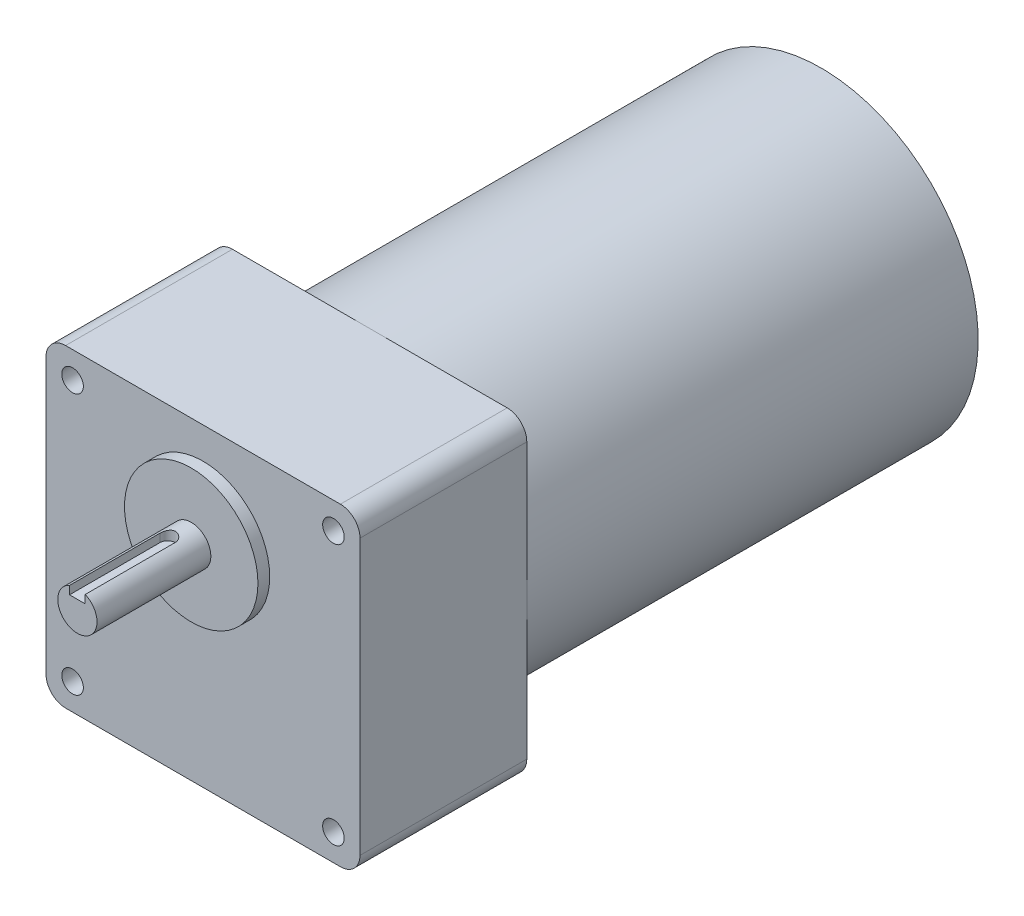
SolidWorks part; units mm, degrees
ref_plane "정면" through (0, 0, 0) normal (0, 0, 1) x (1, 0, 0)
ref_plane "윗면" through (0, 0, 0) normal (0, 1, 0) x (1, 0, 0)
ref_plane "우측면" through (0, 0, 0) normal (1, 0, 0) x (0, 0, -1)
sketch "스케치1" plane through (0, 0, 0) normal (0, 0, 1) x (1, 0, 0)
  line L1 (-40, 40) -> (40, 40)
  line L2 (-40, 40) -> (-40, -40)
  line L3 (-40, -40) -> (40, -40)
  line L4 (40, 40) -> (40, -40)
  point P0 (0, 0)
  dimension "D1" = 80
  dimension "D2" = 80
extrude "보스-돌출1" add sketch "스케치1" along normal blind 10
sketch "스케치2" plane through (0, 0, 10) normal (0, 0, 1) x (1, 0, 0)
  circle A0 centre (0, 15) radius 17
extrude "보스-돌출2" add sketch "스케치2" along normal blind 3
sketch "스케치3" plane through (0, 0, 13) normal (0, 0, 1) x (1, 0, 0)
  circle A0 centre (0, 15) radius 5
extrude "보스-돌출3" add sketch "스케치3" along normal blind 29
sketch "스케치4" plane through (0, 0, 42) normal (0, 0, 1) x (1, 0, 0)
  line L1 (0, 17.5) -> (-2, 17.5)
  line L2 (0, 17.5) -> (2, 17.5)
  line L3 (-2, 17.5) -> (-2, 20.9127)
  line L4 (-2, 20.9127) -> (2, 20.9127)
  line L5 (2, 20.9127) -> (2, 17.5)
extrude "컷-돌출1" cut sketch "스케치4" against normal blind 23
ref_plane "평면1" through (0, 20, 0) normal (0, 1, 0) x (1, 0, 0)
sketch "스케치6" plane through (0, 20, 0) normal (0, 1, 0) x (1, 0, 0)
  line L1 (-2, -19) -> (-2, -52.4077)
  line L2 (-2, -52.4077) -> (2, -52.4077)
  line L3 (2, -19) -> (2, -42) construction
  line L4 (2, -52.4077) -> (2, -19)
  arc A0 (-2, -19) -> (2, -19) centre (0, -19) cw
extrude "컷-돌출4" cut sketch "스케치6" against normal blind 2.5
sketch "스케치7" plane through (0, 0, 0) normal (0, 0, -1) x (-1, 0, 0)
  line L16 (-40, 40) -> (-40, -40)
  line L17 (-40, -40) -> (40, -40)
  line L18 (40, -40) -> (40, 40)
  line L19 (40, 40) -> (-40, 40)
  line L20 (-40, 40) -> (-40, -40)
  line L21 (-40, -40) -> (40, -40)
  line L22 (40, -40) -> (40, 40)
  line L23 (40, 40) -> (-40, 40)
  dimension "D1" = 0
extrude "보스-돌출6" add sketch "스케치7" along normal blind 32.5
sketch "스케치10" plane through (0, 0, -32.5) normal (0, 0, -1) x (-1, 0, 0)
  circle A0 centre (0, 0) radius 40
extrude "보스-돌출7" add sketch "스케치10" along normal blind 115
sketch "스케치11" plane through (0, 0, -147.5) normal (0, 0, -1) x (-1, 0, 0)
  circle A0 centre (0, 0) radius 14
  dimension "D1" = 28
extrude "보스-돌출8" add sketch "스케치11" along normal blind 5
sketch "스케치12" plane through (0, 0, 10) normal (0, 0, 1) x (1, 0, 0)
  line L0 (-33.234, 33.234) -> (0, 0) construction
  circle A0 centre (33.234, 33.234) radius 2.75
  circle A1 centre (-33.234, 33.234) radius 2.75
  circle A2 centre (-33.234, -33.234) radius 2.75
  circle A3 centre (33.234, -33.234) radius 2.75
  point P0 (0, 0)
  dimension "D3" = 5.5
  dimension "D1" = 5.5
  dimension "D2" = 5.5
  dimension "D4" = 5.5
  dimension "D5" = 47
  dimension "D6" = 47
  dimension "D7" = 47
  dimension "D8" = 47
extrude "컷-돌출5" cut sketch "스케치12" against normal through all
fillet "필렛1" radius 5 4 edges at (-40, 40, -11.25) (-40, -40, -11.25) (40, -40, -11.25) (40, 40, -11.25)
